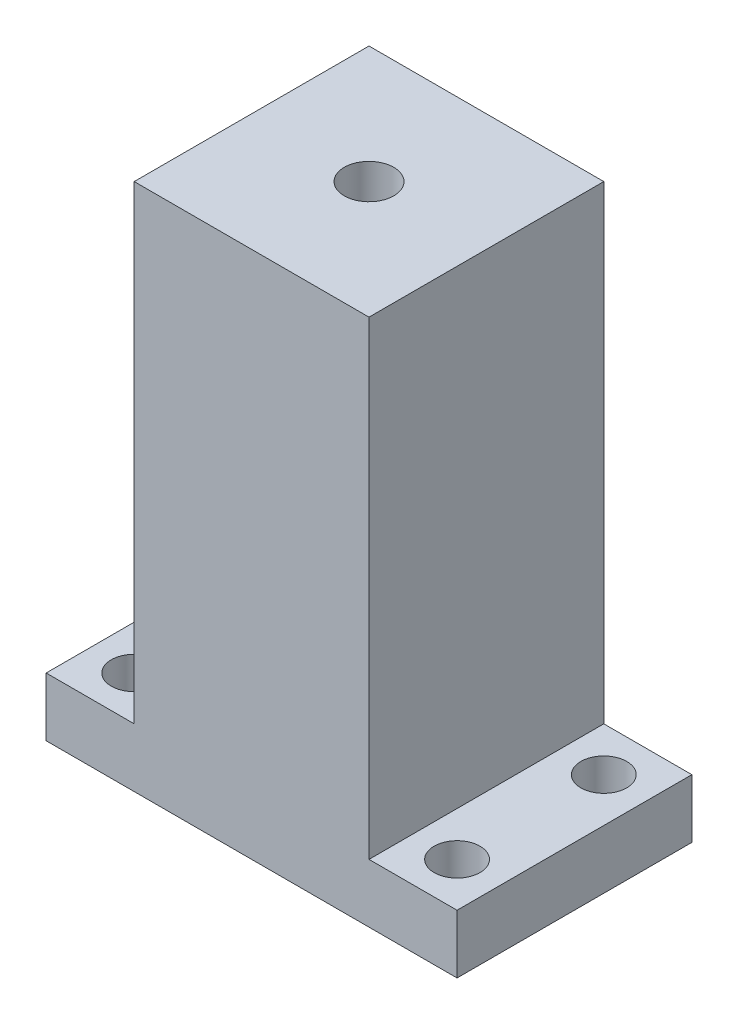
SolidWorks part; units mm, degrees
ref_plane "Front Plane" through (0, 0, 0) normal (0, 0, 1) x (1, 0, 0)
ref_plane "Top Plane" through (0, 0, 0) normal (0, 1, 0) x (1, 0, 0)
ref_plane "Right Plane" through (0, 0, 0) normal (1, 0, 0) x (0, 0, -1)
sketch "Sketch1" plane through (0, 0, 0) normal (0, 1, 0) x (1, 0, 0)
  line L1 (-44.45, -25.4) -> (44.45, -25.4)
  line L2 (-44.45, -25.4) -> (-44.45, 25.4)
  line L3 (-44.45, 25.4) -> (44.45, 25.4)
  line L4 (44.45, -25.4) -> (44.45, 25.4)
  line L5 (-44.45, -25.4) -> (44.45, 25.4) construction
  line L6 (-44.45, 25.4) -> (44.45, -25.4) construction
  point P0 (0, 0)
  dimension "D1" = 50.8
  dimension "D2" = 88.9
extrude "Boss-Extrude1" add sketch "Sketch1" along normal blind 114.3
sketch "Sketch2" plane through (0, 114.3, 0) normal (0, 1, 0) x (1, 0, 0)
  line L0 (44.45, 25.4) -> (-44.45, 25.4) construction
  line L1 (-25.4, -25.4) -> (25.4, -25.4)
  line L2 (-25.4, -25.4) -> (-25.4, 25.4)
  line L3 (-25.4, 25.4) -> (25.4, 25.4)
  line L4 (25.4, -25.4) -> (25.4, 25.4)
  line L5 (-25.4, -25.4) -> (25.4, 25.4) construction
  line L6 (-25.4, 25.4) -> (25.4, -25.4) construction
  point P0 (0, 0)
  dimension "D1" = 50.8
extrude "Cut-Extrude1" cut sketch "Sketch2" against normal blind 101.6 flip side to cut
sketch "Sketch3" plane through (0, 12.7, 0) normal (0, 1, 0) x (1, 0, 0)
  line L0 (-44.45, 25.4) -> (-44.45, -25.4) construction
  line L1 (-25.4, 25.4) -> (-44.45, 25.4) construction
  line L2 (-44.45, -25.4) -> (-25.4, -25.4) construction
  line L3 (44.45, -25.4) -> (44.45, 25.4) construction
  circle A0 centre (-34.925, 15.875) radius 4.9609
  circle A1 centre (-34.925, -15.875) radius 4.9609
  circle A2 centre (34.925, -15.875) radius 4.9609
  circle A3 centre (34.925, 15.875) radius 4.9609
  dimension "D5" = 9.9219
  dimension "D1" = 9.525
  dimension "D2" = 9.525
  dimension "D3" = 9.525
  dimension "D4" = 9.525
extrude "Cut-Extrude2" cut sketch "Sketch3" against normal through all
sketch "Sketch4" plane through (0, 114.3, 0) normal (0, 1, 0) x (1, 0, 0)
  circle A0 centre (0, 0) radius 5.3578
  dimension "D1" = 10.7156
extrude "Cut-Extrude3" cut sketch "Sketch4" against normal blind 41.275
sketch "Sketch5" plane through (0, 0, 0) normal (0, -1, 0) x (1, 0, 0)
  circle A0 centre (0, 0) radius 2.54
extrude "Cut-Extrude4" cut sketch "Sketch5" against normal blind 2.54
